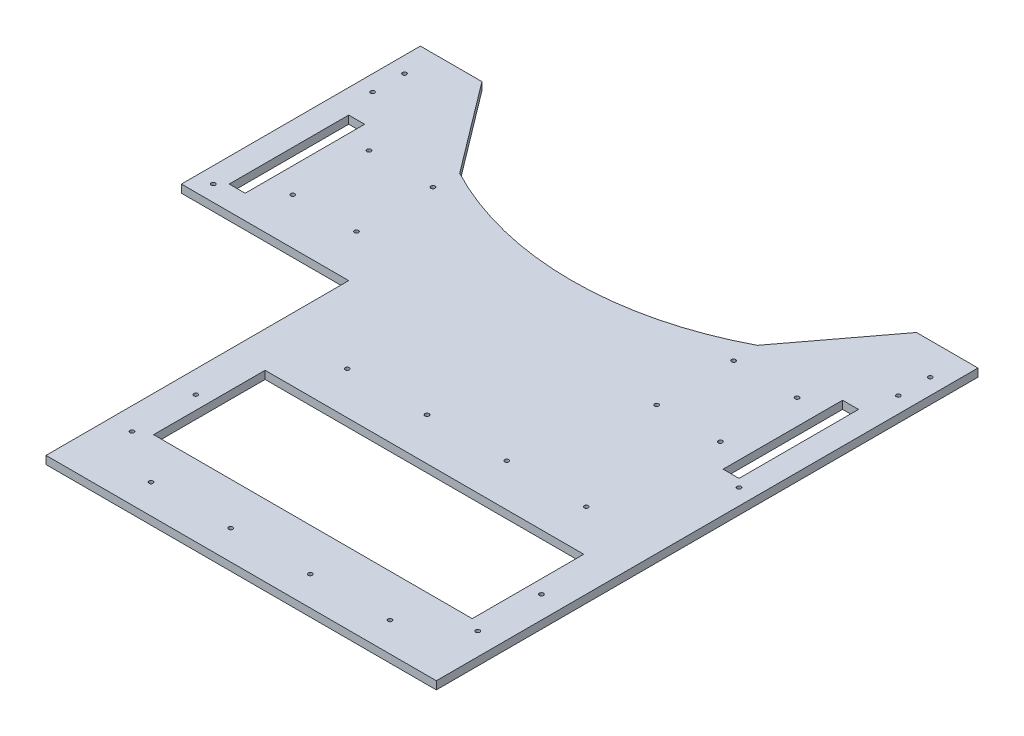
SolidWorks part; units mm, degrees
ref_plane "Front Plane" through (0, 0, 0) normal (0, 0, 1) x (1, 0, 0)
ref_plane "Top Plane" through (0, 0, 0) normal (0, 1, 0) x (1, 0, 0)
ref_plane "Right Plane" through (0, 0, 0) normal (1, 0, 0) x (0, 0, -1)
sketch "Sketch1" plane through (0, 0, 0) normal (0, 1, 0) x (1, 0, 0)
  line L0 (-444.5, 431.8) -> (-395.4569, 431.8)
  line L1 (-311.15, 0) -> (0, 0)
  line L2 (-444.5, 431.8) -> (-444.5, 241.3)
  line L3 (-395.4569, 431.8) -> (-340.9437, 359.5617)
  line L4 (-311.15, 241.3) -> (-311.15, 0)
  line L5 (0, 431.8) -> (0, 0)
  line L6 (-340.9437, 359.5617) -> (-103.5563, 359.5617) construction
  line L7 (-222.25, 359.5617) -> (-222.25, 584.8157) construction
  line L8 (-103.5563, 359.5617) -> (-49.0431, 431.8)
  line L9 (-49.0431, 431.8) -> (0, 431.8)
  line L10 (-444.5, 241.3) -> (-311.15, 241.3)
  line L11 (-282.575, 101.6317) -> (-311.15, 101.6317) construction
  line L12 (-282.575, 57.1818) -> (-28.575, 57.1817)
  line L13 (-282.575, 57.1818) -> (-282.575, 146.0817)
  line L14 (-282.575, 146.0817) -> (-28.575, 146.0817)
  line L15 (-28.575, 57.1817) -> (-28.575, 146.0817)
  line L16 (-28.575, 101.6317) -> (0, 101.6317) construction
  line L17 (-31.75, 355.6) -> (-31.75, 260.35)
  line L18 (-425.45, 355.6) -> (-412.75, 355.6)
  line L19 (-425.45, 355.6) -> (-425.45, 260.35)
  line L20 (-425.45, 260.35) -> (-412.75, 260.35)
  line L21 (-412.75, 355.6) -> (-412.75, 260.35)
  line L22 (-19.05, 260.35) -> (-31.75, 260.35)
  line L23 (-19.05, 355.6) -> (-19.05, 260.35)
  line L24 (-19.05, 355.6) -> (-31.75, 355.6)
  line L25 (-282.575, 101.6317) -> (-28.575, 101.6317) construction
  line L26 (-155.575, 57.1817) -> (-155.575, 146.0817) construction
  arc A0 (-340.9437, 359.5617) -> (-103.5563, 359.5617) centre (-222.25, 584.8157) ccw
  circle A1 centre (-250.825, 23.368) radius 1.632
  circle A2 centre (-187.325, 23.368) radius 1.632
  circle A3 centre (-187.325, 179.8955) radius 1.632
  circle A4 centre (-250.825, 179.8955) radius 1.632
  circle A5 centre (-123.825, 179.8955) radius 1.632
  circle A6 centre (-60.325, 179.8955) radius 1.632
  circle A7 centre (-123.825, 23.368) radius 1.632
  circle A8 centre (-60.325, 23.368) radius 1.6319
  line B0 (0, 457.2) -> (-457.2, 457.2) construction
  line B1 (0, 457.2) -> (0, 0) construction
  line B2 (0, 0) -> (-457.2, 0) construction
  line B3 (-457.2, 457.2) -> (-457.2, 0) construction
  line B4 (-457.2, 228.6) -> (-330.2, 228.6) construction
  line B5 (-330.2, 0) -> (-330.2, 228.6) construction
  arc B6 (-327.0888, 354.3418) -> (-120.3363, 354.3418) centre (-223.7126, 583.1293) ccw construction
  arc B7 (-327.0888, 411.3998) -> (-120.3363, 411.3998) centre (-223.7126, 182.6123) cw construction
  arc B8 (-327.0888, 354.3418) -> (-327.0888, 411.3998) centre (-314.1982, 382.8708) cw construction
  arc B9 (-120.3363, 411.3998) -> (-120.3363, 354.3418) centre (-133.2269, 382.8708) cw construction
  dimension "D14" = 63.5
  dimension "D12" = 3.2639
  dimension "D2" = 254
  dimension "D3" = 88.9
  dimension "D4" = 95.25
  dimension "D5" = 12.7
  dimension "D6" = 19.05
  dimension "D7" = 311.15
  dimension "D8" = 431.8
  dimension "D9" = 444.5
  dimension "D10" = 241.3
  dimension "D11" = 19.05
  dimension "D13" = 156.5275
  dimension "D15" = 63.5
  dimension "D16" = 23.368
sketch_block_instance "Block1-1"
sketch_block "Block1" parameters "D1"=228.6
sketch_block_instance "Block2-1"
sketch_block "Block2"
extrude "Boss-Extrude1" add sketch "Sketch1" along normal blind 6.35 contours A0 L3 L0 L2 L10 L4 L1 L5 L9 L8 L24 L23 L22 L17 L15 L12 L13 L14 L18 L21 L20 L19
sketch "Sketch2" plane through (0, 6.35, 0) normal (0, 1, 0) x (1, 0, 0)
  line L0 (-155.575, 57.1818) -> (-155.575, 168.0977) construction
  line L1 (-282.575, 57.1818) -> (-28.575, 57.1817) construction
  line L2 (-311.15, 0) -> (0, 0) construction
  line L3 (-311.15, 241.3) -> (-311.15, 0) construction
  circle A0 centre (-293.37, 101.6) radius 1.632
  circle A1 centre (-293.37, 50.8) radius 1.632
  circle A2 centre (-17.78, 101.6) radius 1.6319
  circle A3 centre (-17.78, 50.8) radius 1.6319
  dimension "D1" = 3.2639
  dimension "D2" = 50.8
  dimension "D3" = 50.8
  dimension "D4" = 17.78
extrude "Cut-Extrude1" cut sketch "Sketch2" against normal up to next
sketch "Sketch4" plane through (0, 6.35, 0) normal (0, 1, 0) x (1, 0, 0)
  line L0 (-444.5, 336.55) -> (0, 336.55) construction
  line L1 (-444.5, 431.8) -> (-444.5, 241.3) construction
  line L2 (0, 431.8) -> (0, 0) construction
  line L3 (-222.25, 336.55) -> (-222.25, 422.1428) construction
  line L4 (-49.0431, 431.8) -> (0, 431.8) construction
  circle A0 centre (-102.4399, 339.3921) radius 1.6319
  circle A1 centre (-51.6403, 339.1989) radius 1.6319
  circle A2 centre (-102.5562, 278.2389) radius 1.6319
  circle A3 centre (-51.7562, 278.2389) radius 1.632
  circle A4 centre (-392.7438, 278.2389) radius 1.632
  circle A5 centre (-341.9438, 278.2389) radius 1.632
  circle A6 centre (-392.8597, 339.1989) radius 1.632
  circle A7 centre (-342.0601, 339.3921) radius 1.632
  circle A8 centre (-12.7, 406.4) radius 1.632
  circle A9 centre (-12.7, 381) radius 1.632
  circle A10 centre (-12.7, 254) radius 1.632
  circle A11 centre (-431.8, 254) radius 1.6319
  circle A12 centre (-431.8, 381) radius 1.6319
  circle A13 centre (-431.8, 406.4) radius 1.6319
  circle A14 centre (-17.78, 101.6) radius 1.6319 construction
  dimension "D1" = 25.4
  dimension "D2" = 127
  dimension "D3" = 25.4
  dimension "D4" = 12.7
extrude "Cut-Extrude2" cut sketch "Sketch4" against normal up to next
